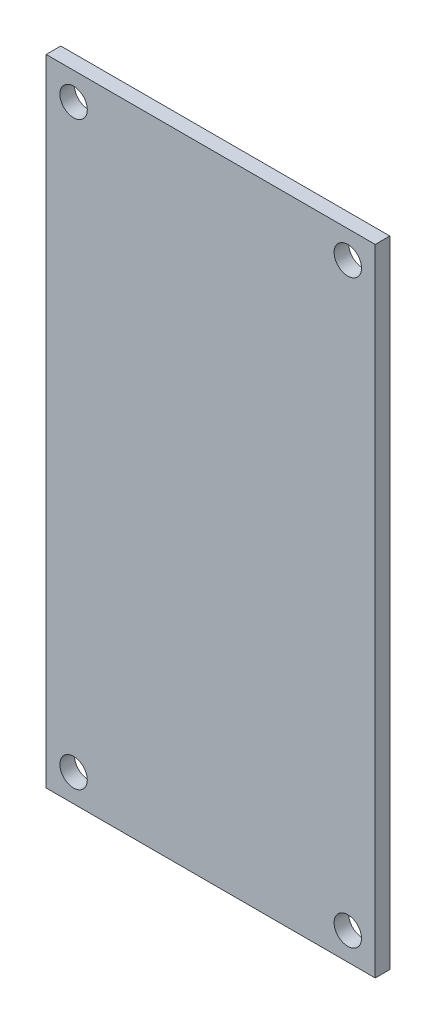
SolidWorks part; units mm, degrees
ref_plane "Front Plane" through (0, 0, 0) normal (0, 0, 1) x (1, 0, 0)
ref_plane "Top Plane" through (0, 0, 0) normal (0, 1, 0) x (1, 0, 0)
ref_plane "Right Plane" through (0, 0, 0) normal (1, 0, 0) x (0, 0, -1)
sketch "Sketch1" plane through (0, 0, 0) normal (0, 0, 1) x (1, 0, 0)
  line L0 (3, 0) -> (3, 69.5) construction
  line L1 (0, 0) -> (36, 0)
  line L2 (0, 0) -> (0, 69.5)
  line L3 (0, 69.5) -> (36, 69.5)
  line L4 (36, 0) -> (36, 69.5)
  line L5 (33, 69.5) -> (33, 0) construction
  line L6 (36, 3) -> (0, 3) construction
  line L7 (0, 66.5) -> (36, 66.5) construction
  circle A0 centre (3, 66.5) radius 1.5
  circle A1 centre (33, 66.5) radius 1.5
  circle A2 centre (33, 3) radius 1.5
  circle A3 centre (3, 3) radius 1.5
  dimension "D7" = 3
  dimension "D1" = 69.5
  dimension "D2" = 36
  dimension "D3" = 3
  dimension "D4" = 3
  dimension "D5" = 3
  dimension "D6" = 3
extrude "Boss-Extrude1" add sketch "Sketch1" along normal blind 1.6
